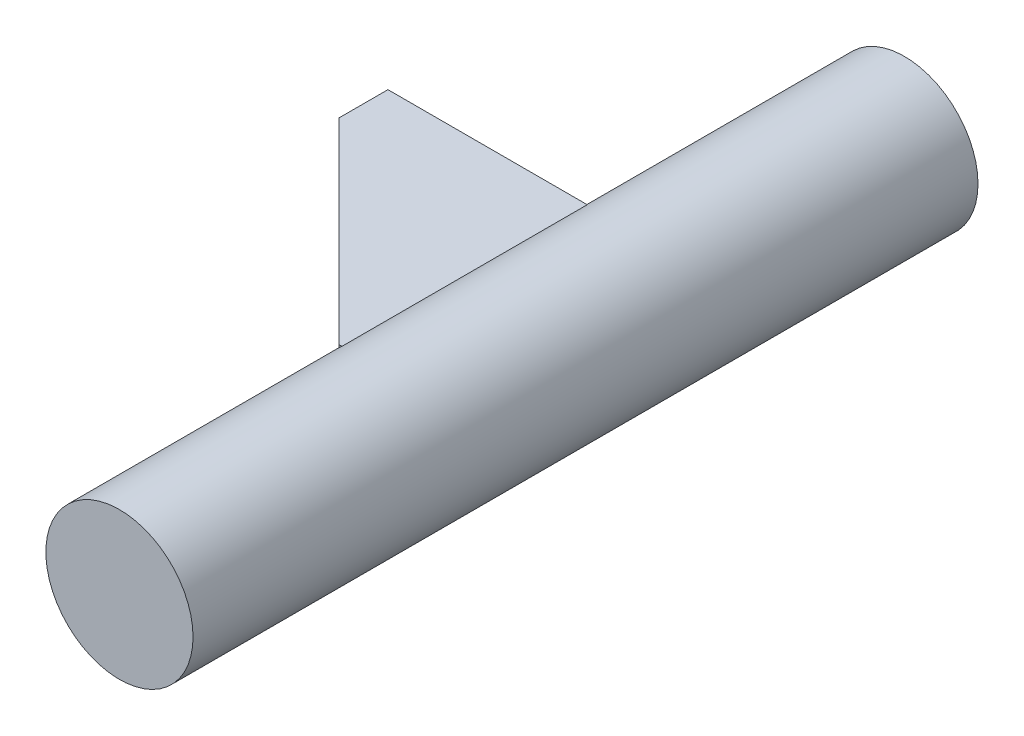
SolidWorks part; units mm, degrees
ref_plane "정면" through (0, 0, 0) normal (0, 0, 1) x (1, 0, 0)
ref_plane "윗면" through (0, 0, 0) normal (0, 1, 0) x (1, 0, 0)
ref_plane "우측면" through (0, 0, 0) normal (1, 0, 0) x (0, 0, -1)
sketch "스케치1" plane through (0, 0, 0) normal (0, 0, 1) x (1, 0, 0)
  circle A0 centre (0, 0) radius 3
  dimension "D1" = 6
extrude "보스-돌출1" add sketch "스케치1" along normal mid plane 32
sketch "스케치2" plane through (0, 0, 0) normal (0, 0, 1) x (1, 0, 0)
  line L1 (-10.0545, 2.2974) -> (0, 2.2974)
  line L2 (-10.0545, 2.2974) -> (-10.0545, -2.0765)
  line L3 (-10.0545, -2.0765) -> (0, -2.0765)
  line L4 (0, 2.2974) -> (0, -2.0765)
extrude "보스-돌출2" add sketch "스케치2" along normal mid plane 10
chamfer "모따기1" distance 8 angle 45 1 edges at (-10.0545, 0.1105, 5)
